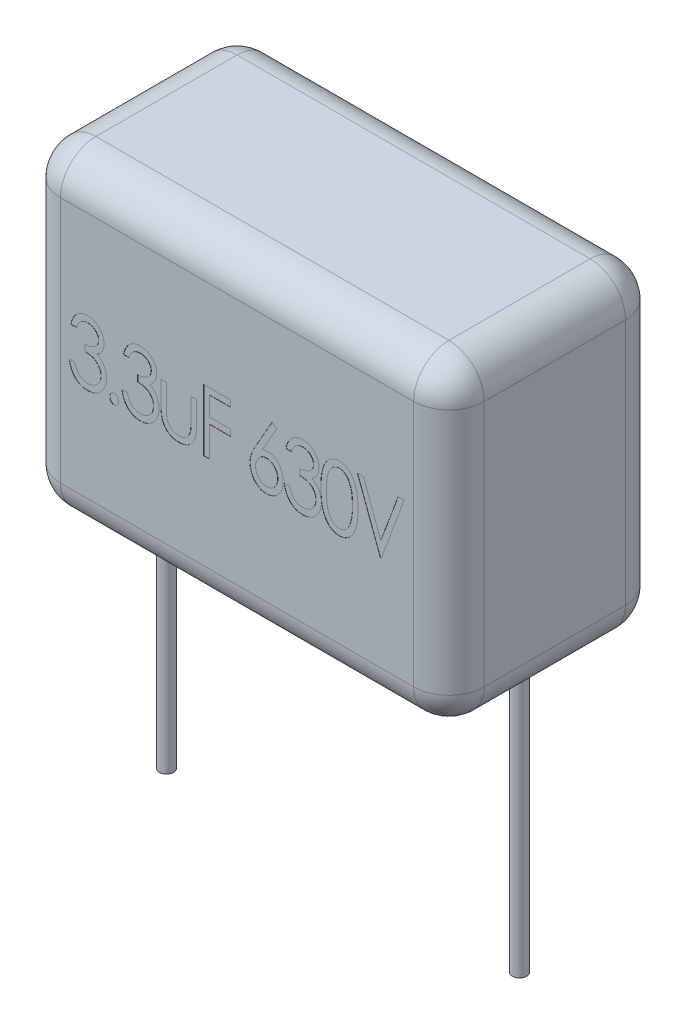
SolidWorks part; units mm, degrees
ref_plane "Front Plane" through (0, 0, 0) normal (0, 0, 1) x (1, 0, 0)
ref_plane "Top Plane" through (0, 0, 0) normal (0, 1, 0) x (1, 0, 0)
ref_plane "Right Plane" through (0, 0, 0) normal (1, 0, 0) x (0, 0, -1)
sketch "Sketch1" plane through (0, 0, 0) normal (1, 0, 0) x (0, 0, -1)
  line L1 (-4, 9) -> (4, 9)
  line L2 (-6, 7) -> (-6, -7)
  line L3 (-4, -9) -> (4, -9)
  line L4 (6, 7) -> (6, -7)
  line L5 (-6, 9) -> (6, -9) construction
  line L6 (-6, -9) -> (6, 9) construction
  arc A0 (4, 9) -> (6, 7) centre (4, 7) cw
  arc A1 (6, -7) -> (4, -9) centre (4, -7) cw
  arc A2 (-6, -7) -> (-4, -9) centre (-4, -7) ccw
  arc A3 (-6, 7) -> (-4, 9) centre (-4, 7) cw
  point P0 (0, 0)
  dimension "D3" = 2
  dimension "D1" = 18
  dimension "D2" = 12
extrude "Boss-Extrude1" add sketch "Sketch1" along normal mid plane 24
fillet "Fillet1" radius 2 16 edges at (-12, 9, 0) (-12, 8.4142, 5.4142) (-12, 0, 6) (-12, -8.4142, 5.4142) (-12, -9, 0) (-12, -8.4142, -5.4142) (-12, 0, -6) (-12, 8.4142, -5.4142) (12, 0, -6) (12, -8.4142, -5.4142) (12, -9, 0) (12, -8.4142, 5.4142) (12, 0, 6) (12, 8.4142, 5.4142) (12, 9, 0) (12, 8.4142, -5.4142)
sketch "Sketch2" plane through (0, 0, 0) normal (0, 1, 0) x (1, 0, 0)
  line L0 (0, 2.8311) -> (0, -1.9116) construction
  circle A0 centre (10, 0) radius 0.4
  circle A1 centre (-10, 0) radius 0.4
  dimension "D1" = 0.8
  dimension "D2" = 20
extrude "Boss-Extrude2" add sketch "Sketch2" against normal blind 24
sketch "Sketch3" plane through (0, 0, 6) normal (0, 0, 1) x (1, 0, 0)
  line L0 (-10, -1.6079) -> (10, -1.6079) construction
  line L1 (-10, 7) -> (-10, -7) construction
  line L2 (10, -7) -> (10, 7) construction
  text T0 "3.3uF 630V" font "Century Gothic" height 3.5
extrude "Cut-Extrude1" cut sketch "Sketch3" against normal blind 0.01
